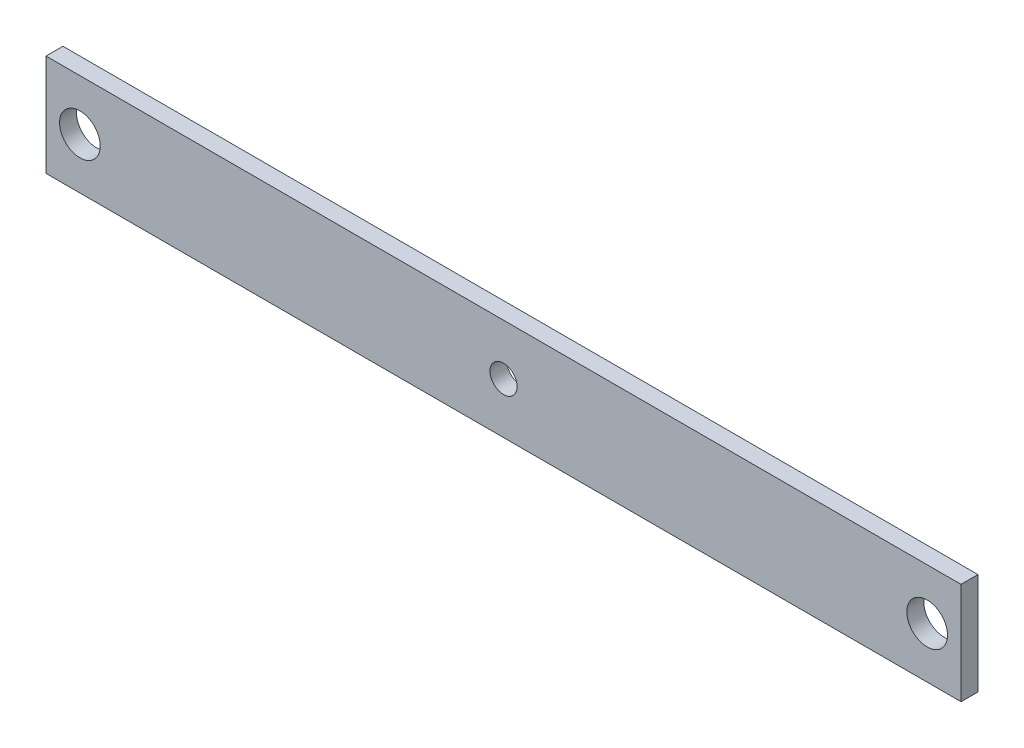
SolidWorks part; units mm, degrees
ref_plane "前视基准面" through (0, 0, 0) normal (0, 0, 1) x (1, 0, 0)
ref_plane "上视基准面" through (0, 0, 0) normal (0, 1, 0) x (1, 0, 0)
ref_plane "右视基准面" through (0, 0, 0) normal (1, 0, 0) x (0, 0, -1)
sketch "草图1" plane through (0, 0, 0) normal (0, 0, 1) x (1, 0, 0)
  line L1 (-135, 15) -> (135, 15)
  line L2 (-135, 15) -> (-135, -15)
  line L3 (-135, -15) -> (135, -15)
  line L4 (135, 15) -> (135, -15)
  line L5 (-135, 15) -> (135, -15) construction
  line L6 (-135, -15) -> (135, 15) construction
  circle A0 centre (-125, 0) radius 6
  circle A1 centre (125, 0) radius 6
  circle A2 centre (0, 0) radius 4
  point P0 (0, 0)
  dimension "D3" = 12
  dimension "D4" = 12
  dimension "D7" = 8
  dimension "D1" = 270
  dimension "D2" = 30
  dimension "D5" = 10
  dimension "D6" = 10
extrude "凸台-拉伸1" add sketch "草图1" along normal blind 5
